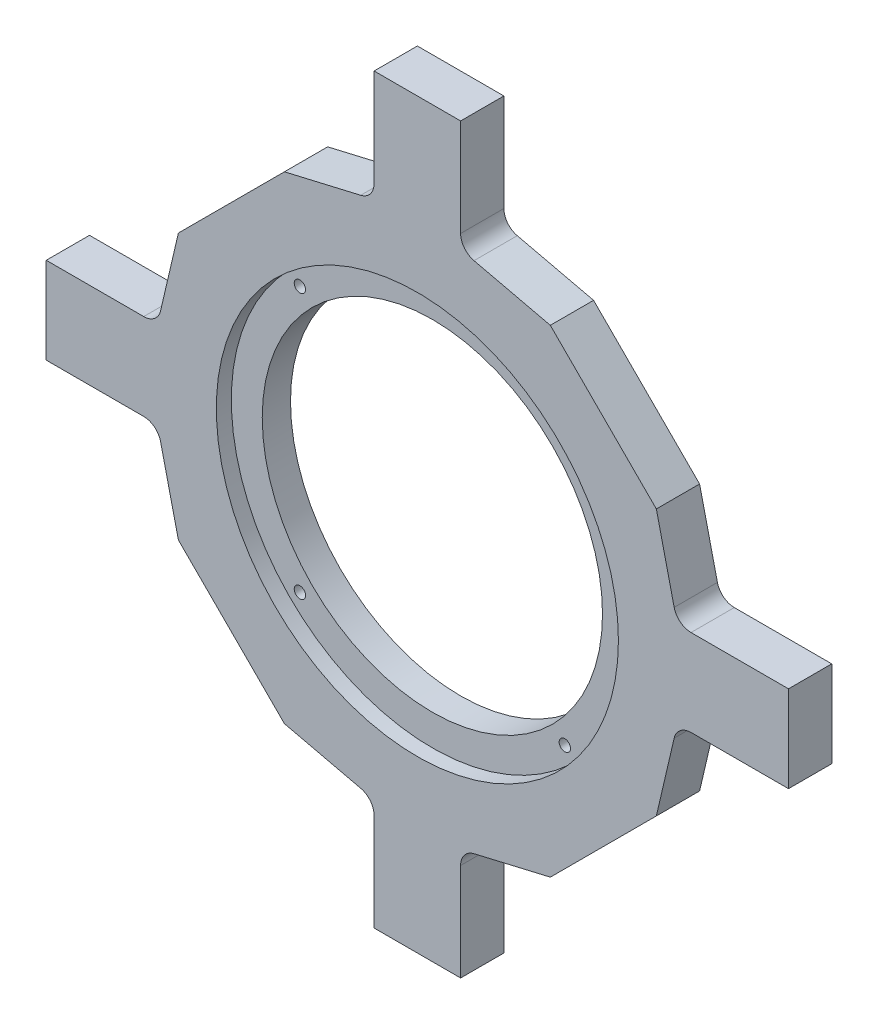
SolidWorks part; units mm, degrees
ref_plane "Front Plane" through (0, 0, 0) normal (0, 0, 1) x (1, 0, 0)
ref_plane "Top Plane" through (0, 0, 0) normal (0, 1, 0) x (1, 0, 0)
ref_plane "Right Plane" through (0, 0, 0) normal (1, 0, 0) x (0, 0, -1)
sketch "Sketch1" plane through (0, 0, 0) normal (0, 0, 1) x (1, 0, 0)
  line L3 (-19.05, 120.5175) -> (-19.05, 163.449)
  line L10 (-120.5175, -19.05) -> (-163.449, -19.05)
  line L11 (-163.449, -19.05) -> (-163.449, 19.05)
  line L12 (-163.449, 19.05) -> (-120.5175, 19.05)
  line L13 (-163.83, 19.431) -> (-163.83, -23.876) construction
  line L14 (-105.2486, 58.5513) -> (-58.5513, 105.2486)
  line L15 (-19.05, 163.449) -> (19.05, 163.449)
  line L16 (-105.2486, 58.5513) -> (-113.0971, 24.9374)
  line L17 (-58.5513, 105.2486) -> (-24.9374, 113.0971)
  line L18 (-81.8999, 81.8999) -> (0, 0) construction
  line L19 (19.05, 163.449) -> (19.05, 120.5175)
  line L20 (58.5513, 105.2486) -> (24.9374, 113.0971)
  line L21 (58.5513, 105.2486) -> (105.2486, 58.5513)
  line L22 (105.2486, 58.5513) -> (113.0971, 24.9374)
  line L23 (120.5175, 19.05) -> (163.449, 19.05)
  line L24 (163.449, 19.05) -> (163.449, -19.05)
  line L25 (163.449, -19.05) -> (120.5175, -19.05)
  line L26 (105.2486, -58.5513) -> (113.0971, -24.9374)
  line L27 (105.2486, -58.5513) -> (58.5513, -105.2486)
  line L28 (58.5513, -105.2486) -> (24.9374, -113.0971)
  line L29 (19.05, -120.5175) -> (19.05, -163.449)
  line L30 (19.05, -163.449) -> (-19.05, -163.449)
  line L31 (-19.05, -163.449) -> (-19.05, -120.5175)
  line L32 (-58.5513, -105.2486) -> (-24.9374, -113.0971)
  line L33 (-58.5513, -105.2486) -> (-105.2486, -58.5513)
  line L34 (-105.2486, -58.5513) -> (-113.0971, -24.9374)
  arc A0 (-24.9374, 113.0971) -> (-113.0971, 24.9374) centre (0, 0) ccw construction
  arc A4 (-120.5175, 19.05) -> (-113.0971, 24.9374) centre (-120.5175, 26.67) ccw
  arc A11 (-19.05, 120.5175) -> (-24.9374, 113.0971) centre (-26.67, 120.5175) cw
  circle A12 centre (0, 0) radius 105.6538 construction
  arc A13 (19.05, 120.5175) -> (24.9374, 113.0971) centre (26.67, 120.5175) ccw
  arc A14 (120.5175, 19.05) -> (113.0971, 24.9374) centre (120.5175, 26.67) cw
  arc A15 (120.5175, -19.05) -> (113.0971, -24.9374) centre (120.5175, -26.67) ccw
  arc A16 (19.05, -120.5175) -> (24.9374, -113.0971) centre (26.67, -120.5175) cw
  arc A17 (-19.05, -120.5175) -> (-24.9374, -113.0971) centre (-26.67, -120.5175) ccw
  arc A18 (-120.5175, -19.05) -> (-113.0971, -24.9374) centre (-120.5175, -26.67) cw
  circle A20 centre (0, 0) radius 62.2533 construction
  point P54 (0, 0)
  dimension "D1" = 10.16
  dimension "D3" = 7.62
  dimension "D4" = 38.1
  dimension "D5" = 0.381
  dimension "D7" = 66.04
  dimension "D8" = 115.824
extrude "Boss-Extrude1" add sketch "Sketch1" along normal blind 19.05
sketch "Sketch2" plane through (0, 0, 19.05) normal (0, 0, 1) x (1, 0, 0)
  circle A0 centre (0, 0) radius 74.93
  dimension "D1" = 149.86
extrude "Cut-Extrude1" cut sketch "Sketch2" against normal through all
sketch "Sketch3" plane through (0, 0, 19.05) normal (0, 0, 1) x (1, 0, 0)
  circle A0 centre (0, 0) radius 88.5464
extrude "Cut-Extrude2" cut sketch "Sketch3" against normal blind 6.604
sketch "Sketch4" plane through (0, 0, 12.446) normal (0, 0, 1) x (1, 0, 0)
  circle A0 centre (-58.3363, 58.3363) radius 2.5
  circle A1 centre (58.3363, 58.3363) radius 2.5
  circle A2 centre (58.3363, -58.3363) radius 2.5
  circle A3 centre (-58.3363, -58.3363) radius 2.5
  dimension "D1" = 5
extrude "Cut-Extrude3" cut sketch "Sketch4" against normal through all
